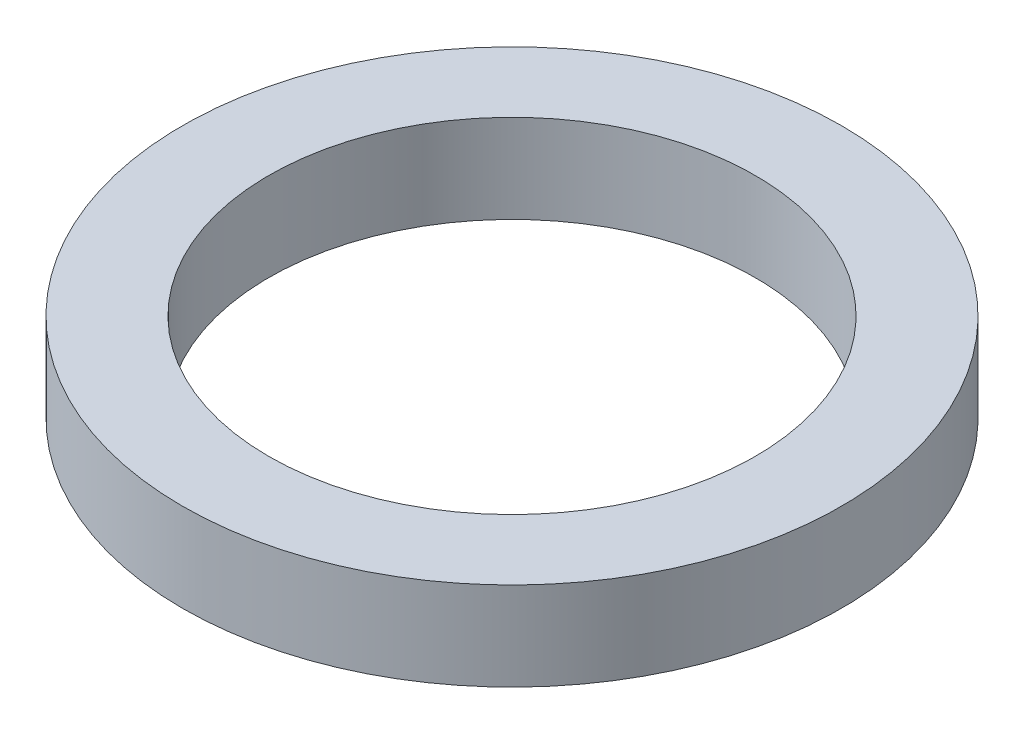
SolidWorks part; units mm, degrees
ref_plane "Front Plane" through (0, 0, 0) normal (0, 0, 1) x (1, 0, 0)
ref_plane "Top Plane" through (0, 0, 0) normal (0, 1, 0) x (1, 0, 0)
ref_plane "Right Plane" through (0, 0, 0) normal (1, 0, 0) x (0, 0, -1)
sketch "Sketch1" plane through (0, 0, 0) normal (0, 1, 0) x (1, 0, 0)
  circle A0 centre (0, 0) radius 7.45
  circle A1 centre (0, 0) radius 5.5
  dimension "D1" = 14.9
  dimension "D2" = 11
extrude "Boss-Extrude1" add sketch "Sketch1" along normal blind 2
